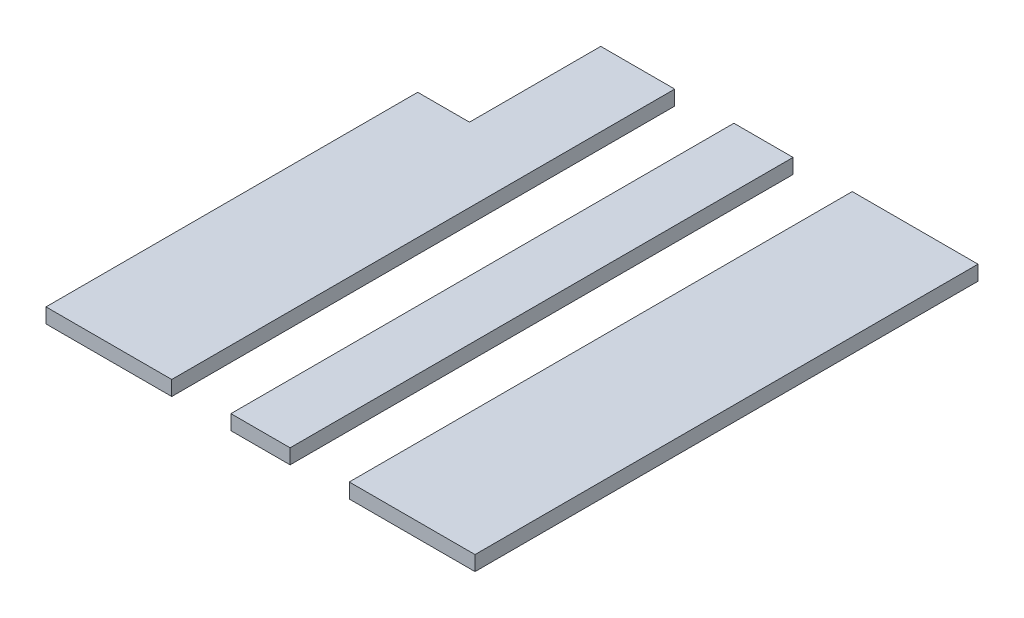
SolidWorks part; units mm, degrees
ref_plane "front" through (0, 0, 0) normal (0, 0, 1) x (1, 0, 0)
ref_plane "top" through (0, 0, 0) normal (0, 1, 0) x (1, 0, 0)
ref_plane "right" through (0, 0, 0) normal (1, 0, 0) x (0, 0, -1)
sketch "Sketch1" plane through (0, 0, 0) normal (0, 1, 0) x (1, 0, 0)
  line L0 (171.45, 469.9) -> (-19.05, 469.9)
  line L1 (-180.975, 482.6) -> (180.975, 482.6)
  line L2 (-196.85, 466.725) -> (-196.85, 15.875)
  line L3 (-180.975, 0) -> (180.975, 0)
  line L4 (196.85, 466.725) -> (196.85, 15.875)
  line L5 (-44.45, 444.5) -> (-44.45, 368.3)
  line L6 (-59.4796, 345.1135) -> (-111.9704, 321.6365)
  line L7 (-127, 298.45) -> (-127, 95.25)
  line L8 (-117.3758, 75.3431) -> (-79.4742, 45.3069)
  line L9 (-69.85, 25.4) -> (-69.85, 0)
  line L10 (0, 60.6632) -> (0, 195.7443) construction
  line L15 (69.85, 25.4) -> (69.85, 0)
  line L16 (117.3758, 75.3431) -> (79.4742, 45.3069)
  line L17 (127, 298.45) -> (127, 95.25)
  line L18 (59.4796, 345.1135) -> (111.9704, 321.6365)
  line L19 (44.45, 368.3) -> (44.45, 381)
  line L20 (69.85, 406.4) -> (171.45, 406.4)
  line L21 (184.15, 419.1) -> (184.15, 457.2)
  arc A0 (-19.05, 469.9) -> (-44.45, 444.5) centre (-19.05, 444.5) ccw
  arc A1 (-44.45, 368.3) -> (-59.4796, 345.1135) centre (-69.85, 368.3) cw
  arc A2 (-111.9704, 321.6365) -> (-127, 298.45) centre (-101.6, 298.45) ccw
  arc A3 (-127, 95.25) -> (-117.3758, 75.3431) centre (-101.6, 95.25) ccw
  arc A4 (-79.4742, 45.3069) -> (-69.85, 25.4) centre (-95.25, 25.4) cw
  arc A7 (79.4742, 45.3069) -> (69.85, 25.4) centre (95.25, 25.4) ccw
  arc A8 (127, 95.25) -> (117.3758, 75.3431) centre (101.6, 95.25) cw
  arc A9 (111.9704, 321.6365) -> (127, 298.45) centre (101.6, 298.45) cw
  arc A10 (44.45, 368.3) -> (59.4796, 345.1135) centre (69.85, 368.3) ccw
  arc A13 (44.45, 381) -> (69.85, 406.4) centre (69.85, 381) cw
  arc A14 (171.45, 406.4) -> (184.15, 419.1) centre (171.45, 419.1) ccw
  arc A15 (171.45, 469.9) -> (184.15, 457.2) centre (171.45, 457.2) cw
  circle A16 centre (152.4, 431.8) radius 22.225
  arc A17 (180.975, 0) -> (196.85, 15.875) centre (180.975, 15.875) ccw
  arc A18 (180.975, 482.6) -> (196.85, 466.725) centre (180.975, 466.725) cw
  arc A19 (-180.975, 482.6) -> (-196.85, 466.725) centre (-180.975, 466.725) ccw
  arc A20 (-196.85, 15.875) -> (-180.975, 0) centre (-180.975, 15.875) ccw
  dimension "D3" = 25.4
  dimension "D4" = 25.4
  dimension "D5" = 25.4
  dimension "D6" = 25.4
  dimension "D7" = 25.4
  dimension "D8" = 25.4
  dimension "D9" = 25.4
  dimension "D10" = 12.7
  dimension "D11" = 12.7
  dimension "D14" = 44.45
  dimension "D15" = 15.875
  dimension "D1" = 393.7
  dimension "D2" = 203.2
  dimension "D12" = 12.7
  dimension "D13" = 12.7
  dimension "D16" = 12.7
  dimension "D17" = 69.85
  dimension "D18" = 69.85
  dimension "D19" = 88.9
  dimension "D20" = 63.5
  dimension "D21" = 139.7
  dimension "D22" = 254
  dimension "D23" = 482.6
  dimension "D24" = 431.8
  dimension "D25" = 152.4
sketch "Sketch2" plane through (0, 0, 0) normal (0, 1, 0) x (1, 0, 0)
  line L0 (180.975, 469.9) -> (-180.975, 469.9)
  line L1 (-184.15, 466.725) -> (-184.15, 15.875)
  line L2 (-180.975, 12.7) -> (180.975, 12.7)
  line L3 (184.15, 15.875) -> (184.15, 466.725)
  line L4 (180.975, 482.6) -> (-180.975, 482.6)
  line L5 (-196.85, 466.725) -> (-196.85, 15.875)
  line L6 (-180.975, 0) -> (180.975, 0)
  line L7 (196.85, 15.875) -> (196.85, 466.725)
  line L8 (180.975, 482.6) -> (-180.975, 482.6) construction
  line L9 (-196.85, 466.725) -> (-196.85, 15.875) construction
  line L10 (-180.975, 0) -> (180.975, 0) construction
  line L11 (196.85, 15.875) -> (196.85, 466.725) construction
  line L12 (-184.15, 466.725) -> (-184.15, 469.9)
  line L13 (-180.975, 469.9) -> (-184.15, 469.9)
  line L14 (180.975, 469.9) -> (184.15, 469.9)
  line L15 (184.15, 466.725) -> (184.15, 469.9)
  arc A1 (-184.15, 15.875) -> (-180.975, 12.7) centre (-180.975, 15.875) ccw
  arc A2 (180.975, 12.7) -> (184.15, 15.875) centre (180.975, 15.875) ccw
  arc A4 (180.975, 0) -> (196.85, 15.875) centre (180.975, 15.875) ccw
  arc A5 (180.975, 0) -> (196.85, 15.875) centre (180.975, 15.875) ccw construction
  arc A6 (-196.85, 15.875) -> (-180.975, 0) centre (-180.975, 15.875) ccw
  arc A7 (-196.85, 15.875) -> (-180.975, 0) centre (-180.975, 15.875) ccw construction
  arc A8 (-180.975, 482.6) -> (-196.85, 466.725) centre (-180.975, 466.725) ccw
  arc A9 (-180.975, 482.6) -> (-196.85, 466.725) centre (-180.975, 466.725) ccw construction
  arc A10 (196.85, 466.725) -> (180.975, 482.6) centre (180.975, 466.725) ccw
  arc A11 (196.85, 466.725) -> (180.975, 482.6) centre (180.975, 466.725) ccw construction
  arc A16 (-180.975, 469.9) -> (-184.15, 466.725) centre (-180.975, 466.725) ccw construction
  arc A17 (184.15, 466.725) -> (180.975, 469.9) centre (180.975, 466.725) ccw construction
  dimension "D1" = 0
  dimension "D2" = 12.7
extrude "Extrude2" add sketch "Sketch2" along normal blind 12.7
sketch "Sketch3" plane through (0, 0, 0) normal (0, 1, 0) x (1, 0, 0)
  line L1 (-231.561, 38.1) -> (231.561, 38.1)
  line L2 (-231.561, 38.1) -> (-231.561, -48.6359)
  line L3 (-231.561, -48.6359) -> (231.561, -48.6359)
  line L4 (231.561, 38.1) -> (231.561, -48.6359)
  point P4 (0, -48.6359)
  dimension "D1" = 38.1
extrude "Cut-Extrude1" cut sketch "Sketch3" along normal through all
sketch "Sketch4" plane through (0, 0, 0) normal (0, 1, 0) x (1, 0, 0)
  line L0 (-198.4502, 488.95) -> (-198.4502, 318.6317) construction
  line L1 (-180.975, 482.6) -> (180.975, 482.6) construction
  line L2 (-165.1, 408.0002) -> (-203.3652, 408.0002)
  line L3 (-184.15, 469.9) -> (-184.15, 38.1) construction
  line L4 (-203.3652, 408.0002) -> (-203.3652, 357.2002)
  line L5 (-223.49, 404.8252) -> (-139.7, 404.8252) construction
  line L6 (-223.49, 404.8252) -> (-223.49, 360.3752) construction
  line L7 (-223.49, 360.3752) -> (-139.7, 360.3752) construction
  line L8 (-139.7, 404.8252) -> (-139.7, 360.3752) construction
  line L9 (-203.3652, 357.2002) -> (-165.1, 357.2002)
  arc A0 (-165.1, 357.2002) -> (-165.1, 408.0002) centre (-165.1, 382.6002) ccw
  point P11 (-139.7, 382.6002)
  dimension "D3" = 50.8
  dimension "D1" = 99.9998
  dimension "D2" = 14.3002
  dimension "D4" = 58.7502
  dimension "D5" = 44.45
extrude "Cut-Extrude2" cut sketch "Sketch4" along normal through all
sketch "Sketch5" plane through (0, 0, 0) normal (0, 1, 0) x (1, 0, 0)
  line L0 (0, 0) -> (0, -120.2795) construction
  line L1 (-76.2, 486.7808) -> (-25.4, 486.7808)
  line L2 (-76.2, 486.7808) -> (-76.2, 10.0767)
  line L3 (-76.2, 10.0767) -> (-25.4, 10.0767)
  line L4 (-25.4, 486.7808) -> (-25.4, 10.0767)
  line L5 (25.4, 486.7808) -> (25.4, 10.0767)
  line L6 (76.2, 10.0767) -> (25.4, 10.0767)
  line L7 (76.2, 486.7808) -> (76.2, 10.0767)
  line L8 (76.2, 486.7808) -> (25.4, 486.7808)
  line L9 (-184.15, 357.2002) -> (-184.15, 38.1) construction
  point P11 (-50.8, 10.0767)
  dimension "D1" = 50.8
  dimension "D2" = 50.8
  dimension "D3" = 107.95
extrude "Cut-Extrude3" cut sketch "Sketch5" along normal through all contours L4 L3 L2 L1 | L5 L6 L7 L8
sketch "Sketch6" plane through (0, 12.7, 0) normal (0, 1, 0) x (-1, 0, 0)
  line L0 (184.15, -357.2002) -> (139.7, -357.2002)
  line L1 (139.7, -357.2002) -> (139.7, -469.9)
  line L3 (76.2, -469.9) -> (184.15, -469.9) construction
  dimension "D2" = 44.45
extrude "Cut-Extrude4" cut sketch "Sketch6" against normal through all and the other way through all
